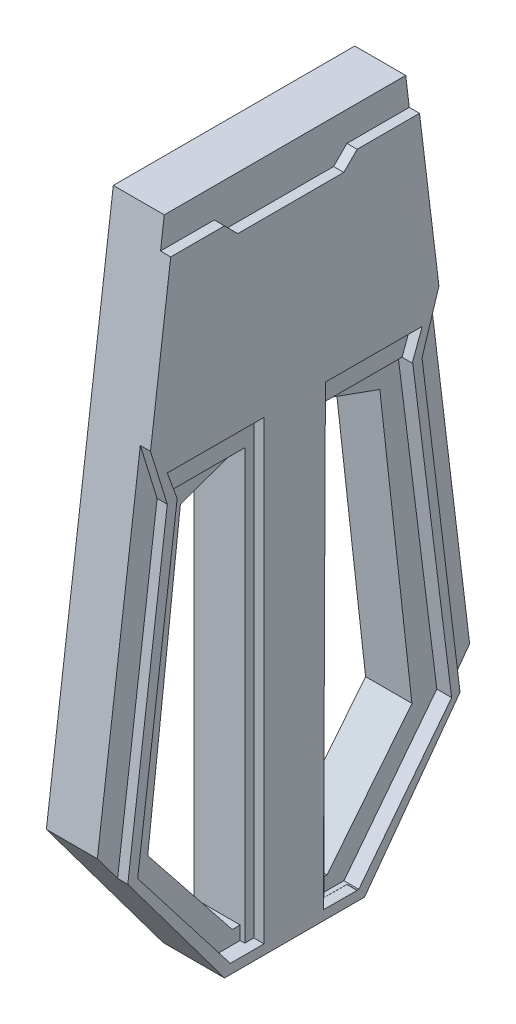
SolidWorks part; units mm, degrees
ref_plane "Front Plane" through (0, 0, 0) normal (0, 0, 1) x (1, 0, 0)
ref_plane "Top Plane" through (0, 0, 0) normal (0, 1, 0) x (1, 0, 0)
ref_plane "Right Plane" through (0, 0, 0) normal (1, 0, 0) x (0, 0, -1)
sketch "Sketch1" plane through (0, 0, 0) normal (1, 0, 0) x (0, 0, -1)
  line L0 (-268.3639, -157.2454) -> (306.9694, -157.2454) construction
  line L1 (0, 0) -> (30.2276, 0)
  line L2 (30.2276, 0) -> (55.0996, 33.7985)
  line L3 (55.0996, 33.7985) -> (41.3066, 146.9171)
  line L4 (41.3066, 146.9171) -> (-10.7931, 146.9171)
  line L5 (-10.7931, 146.9171) -> (-25.2375, 33.7985)
  line L6 (-25.2375, 33.7985) -> (0, 0)
  line L7 (15.7806, -32.7217) -> (15.7806, 0)
  dimension "D1" = 33.7985
  dimension "D2" = 146.9171
  dimension "D3" = 25.2375
  dimension "D4" = 80.3371
  dimension "D5" = 32.7217
extrude "Boss-Extrude1" add sketch "Sketch1" along normal blind 13.2 contours L1 L2 L3 L4 L5 L6
sketch "Sketch2" plane through (13.2, 0, 0) normal (1, 0, 0) x (0, 0, -1)
  line L0 (-15.9661, 106.4056) -> (-12.3445, 94.7038)
  line L1 (-10.7931, 146.9171) -> (-25.2375, 33.7985) construction
  line L2 (-12.3445, 94.7038) -> (-20.8687, 27.9478)
  line L3 (-25.2375, 33.7985) -> (0, 0) construction
  line L4 (-20.8687, 27.9478) -> (-25.2375, 33.7985)
  line L5 (-25.2375, 33.7985) -> (-15.9661, 106.4056)
  line L6 (14.6053, -146.9171) -> (15.2568, 146.9171)
  line L7 (-12.3445, 100.5506) -> (8.5293, 100.5044)
  line L8 (41.3066, 146.9171) -> (-10.7931, 146.9171) construction
  line L13 (-12.3445, 100.5506) -> (-10.2107, 94.7038)
  line L14 (-10.2107, 94.7038) -> (-18.735, 27.9478)
  line L15 (-18.735, 27.9478) -> (1.2471, 2.1155)
  line L16 (1.2471, 2.1155) -> (8.5293, 2.1155)
  line L17 (50.8544, 27.7888) -> (55.2491, 33.6201)
  line L18 (42.6262, 94.5819) -> (50.8544, 27.7888)
  line L19 (46.2997, 106.2675) -> (42.6262, 94.5819)
  line L20 (8.5293, 100.5044) -> (8.5293, 2.1155)
  line L21 (55.2491, 33.6201) -> (46.2997, 106.2675)
  line L22 (48.7206, 27.7982) -> (28.6242, 2.0548)
  line L23 (40.4924, 94.5913) -> (48.7206, 27.7982)
  line L24 (42.6522, 100.4287) -> (40.4924, 94.5913)
  line L25 (42.6522, 100.4287) -> (21.7784, 100.475)
  line L26 (21.7784, 100.475) -> (21.342, 2.0871)
  line L27 (28.6242, 2.0548) -> (21.342, 2.0871)
  line L34 (-10.7931, 146.9171) -> (-11.6051, 140.5581)
  line L35 (-11.6051, 140.5581) -> (0, 140.5581)
  line L36 (0, 140.5581) -> (2.8852, 137.6728)
  line L37 (41.3066, 146.9171) -> (42.082, 140.5581)
  line L38 (55.0996, 33.7985) -> (41.3066, 146.9171) construction
  line L39 (42.082, 140.5581) -> (28.6242, 140.5581)
  line L40 (28.6242, 140.5581) -> (25.7389, 137.6728)
  line L41 (25.7389, 137.6728) -> (2.8852, 137.6728)
  line L42 (-10.7931, 146.9171) -> (41.3066, 146.9171)
  point P12 (14.931, 0)
  line M6 (-25.2375, 33.7985) -> (0, 0)
  line M8 (30.2276, 0) -> (55.0996, 33.7985)
  line M9 (55.0996, 33.7985) -> (41.3066, 146.9171)
  line M10 (41.3066, 146.9171) -> (-10.7931, 146.9171)
  line M11 (-10.7931, 146.9171) -> (-25.2375, 33.7985)
extrude "Cut-Extrude1" cut sketch "Sketch2" against normal blind 2.2 contours L27 L22 L23 L24 L25 L26 | L19 L18 M9 M8 | L2 L0 M11 M6 | L20 L7 L13 L14 L15 L16 | L41 L6 L35 L36 M10 M11 | L41 L40 L39 L6 M9 M10
sketch "Sketch5" plane through (13.2, 0, 0) normal (1, 0, 0) x (0, 0, -1)
  line L1 (6.5824, 94.7038) -> (-10.2107, 94.7038)
  line L8 (15.2568, 146.9171) -> (15.1138, 0) construction
  line L9 (41.3066, 146.9171) -> (-10.7931, 146.9171) construction
  line L10 (0, 0) -> (30.2276, 0) construction
  line L12 (6.5824, 94.7038) -> (6.5824, 2.1155)
  line L13 (1.2471, 2.1155) -> (8.5293, 2.1155) construction
  line L14 (6.5824, 2.1155) -> (1.2471, 2.1155)
  line L15 (1.2471, 2.1155) -> (-18.735, 27.9478)
  line L16 (-18.735, 27.9478) -> (-10.2107, 94.7038)
  line L19 (49.0169, 27.8818) -> (40.6226, 94.6543)
  line L20 (28.9845, 2.0885) -> (49.0169, 27.8818)
  line L21 (23.6493, 2.0989) -> (28.9845, 2.0885)
  line L22 (23.8295, 94.687) -> (23.6493, 2.0989)
  line L23 (23.8295, 94.687) -> (40.6226, 94.6543)
extrude "Cut-Extrude5" cut sketch "Sketch5" against normal blind 3.2
sketch "Sketch8" plane through (10, 0, 0) normal (1, 0, 0) x (0, 0, -1)
  line L0 (6.5824, 94.7038) -> (-6.3142, 90.0651)
  line L1 (-6.3142, 90.0651) -> (-13.365, 27.9478)
  line L2 (-13.365, 27.9478) -> (4.8882, 5.0202)
  line L3 (4.8882, 5.0202) -> (6.5824, 5.0202)
  line L4 (6.5824, 2.1155) -> (6.5824, 94.7038) construction
  line L5 (6.5824, 5.0202) -> (6.5824, 94.7038)
  line L6 (15.2568, 146.9171) -> (15.1138, 0) construction
  line L7 (41.3066, 146.9171) -> (-10.7931, 146.9171) construction
  line L8 (0, 0) -> (30.2276, 0) construction
  line L9 (25.3491, 5.0003) -> (23.6549, 5.0036)
  line L10 (43.6469, 27.8923) -> (25.3491, 5.0003)
  line L11 (36.717, 90.0232) -> (43.6469, 27.8923)
  line L12 (23.8295, 94.687) -> (36.717, 90.0232)
  line L13 (23.6549, 5.0036) -> (23.8295, 94.687)
extrude "Cut-Extrude7" cut sketch "Sketch8" against normal blind 47.2
